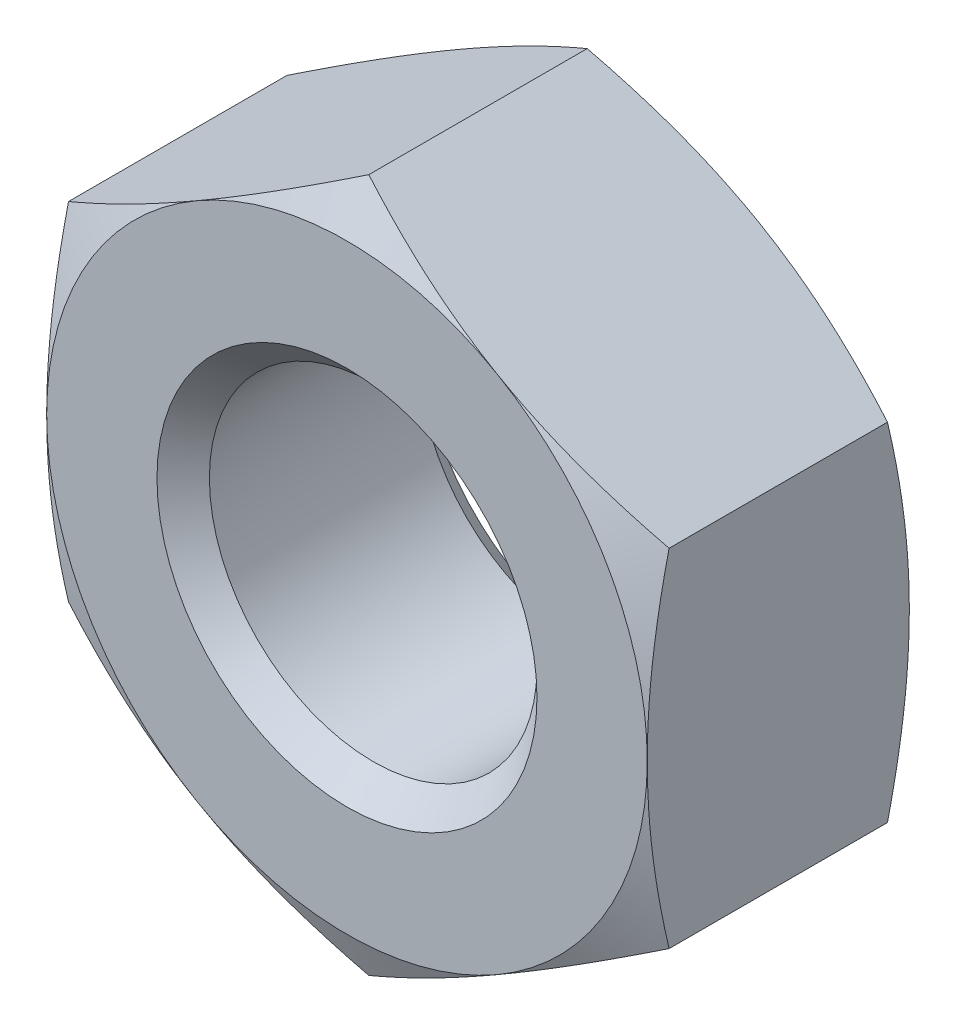
SolidWorks part; units mm, degrees
material "Plain Carbon Steel"
ref_plane "Front Plane" through (0, 0, 0) normal (0, 0, 1) x (1, 0, 0)
ref_plane "Top Plane" through (0, 0, 0) normal (0, 1, 0) x (1, 0, 0)
ref_plane "Right Plane" through (0, 0, 0) normal (1, 0, 0) x (0, 0, -1)
sketch "Sketch1" plane through (0, 0, 0) normal (0, 0, 1) x (1, 0, 0)
  line L1 (0, -3.1754) -> (2.75, -1.5877)
  line L2 (2.75, -1.5877) -> (2.75, 1.5877)
  line L3 (2.75, 1.5877) -> (0, 3.1754)
  line L4 (0, 3.1754) -> (-2.75, 1.5877)
  line L5 (-2.75, 1.5877) -> (-2.75, -1.5877)
  line L6 (-2.75, -1.5877) -> (0, -3.1754)
  circle A0 centre (0, 0) radius 2.75 construction
  circle A1 centre (0, 0) radius 1.5
  dimension "D2" = 3
  dimension "D1" = 5.5
extrude "Boss-Extrude1" add sketch "Sketch1" along normal blind 2.4
sketch "Sketch2" plane through (0, 0, 0) normal (1, 0, 0) x (0, 0, -1)
  line L0 (-2.4, 3.1754) -> (-2.4, 2.75)
  line L1 (-2.4, 1.5877) -> (-2.4, 3.1754) construction
  line L2 (-2.4, 2.75) -> (-2.2, 3.1754)
  line L3 (-2.4, 3.1754) -> (0, 3.1754) construction
  line L4 (-2.2, 3.1754) -> (-2.4, 3.1754)
  line L5 (-0.2, 3.1754) -> (0, 3.1754)
  line L6 (0, 3.1754) -> (0, 2.75)
  line L7 (0, 1.5877) -> (0, 3.1754) construction
  line L8 (0, 2.75) -> (-0.2, 3.1754)
  line L9 (-2.2, 3.1754) -> (-2, 3.1754) construction
  line L10 (-2, 3.1754) -> (-1.8, 3.1754) construction
  line L11 (-1.8, 3.1754) -> (-1.6, 3.1754) construction
  line L12 (-1.6, 3.1754) -> (-1.4, 3.1754) construction
  line L13 (-1.4, 3.1754) -> (-1.2, 3.1754) construction
  line L14 (-1.2, 3.1754) -> (-1, 3.1754) construction
  line L15 (-1, 3.1754) -> (-0.8, 3.1754) construction
  line L16 (-0.8, 3.1754) -> (-0.6, 3.1754) construction
  line L17 (-0.6, 3.1754) -> (-0.4, 3.1754) construction
  line L18 (0, 0) -> (-2.4, 0) construction
  line L19 (-2.4, -1.5877) -> (-2.4, 1.5877) construction
  line L20 (-2.4, 1.5) -> (-2.16, 1.5)
  line L21 (-2.16, 1.5) -> (-2.4, 1.74)
  line L22 (-2.4, 1.74) -> (-2.4, 1.5)
  line L23 (0, 1.5) -> (-0.24, 1.5)
  line L24 (0, -1.5877) -> (0, 1.5877) construction
  line L25 (-0.24, 1.5) -> (0, 1.74)
  line L26 (0, 1.74) -> (0, 1.5)
  line L29 (-2.16, 1.5) -> (-1.92, 1.5) construction
  line L30 (-1.92, 1.5) -> (-1.68, 1.5) construction
  line L31 (-1.68, 1.5) -> (-1.44, 1.5) construction
  line L32 (-1.44, 1.5) -> (-1.2, 1.5) construction
  line L33 (-1.2, 1.5) -> (-0.96, 1.5) construction
  line L34 (-0.96, 1.5) -> (-0.72, 1.5) construction
  line L35 (-0.72, 1.5) -> (-0.48, 1.5) construction
  line L36 (-0.48, 1.5) -> (-0.24, 1.5) construction
  line L37 (-0.4, 3.1754) -> (-0.2, 3.1754) construction
  dimension "D1" = 5.5
revolve "Cut-Revolve1" cut sketch "Sketch2" angle 360 about L18
